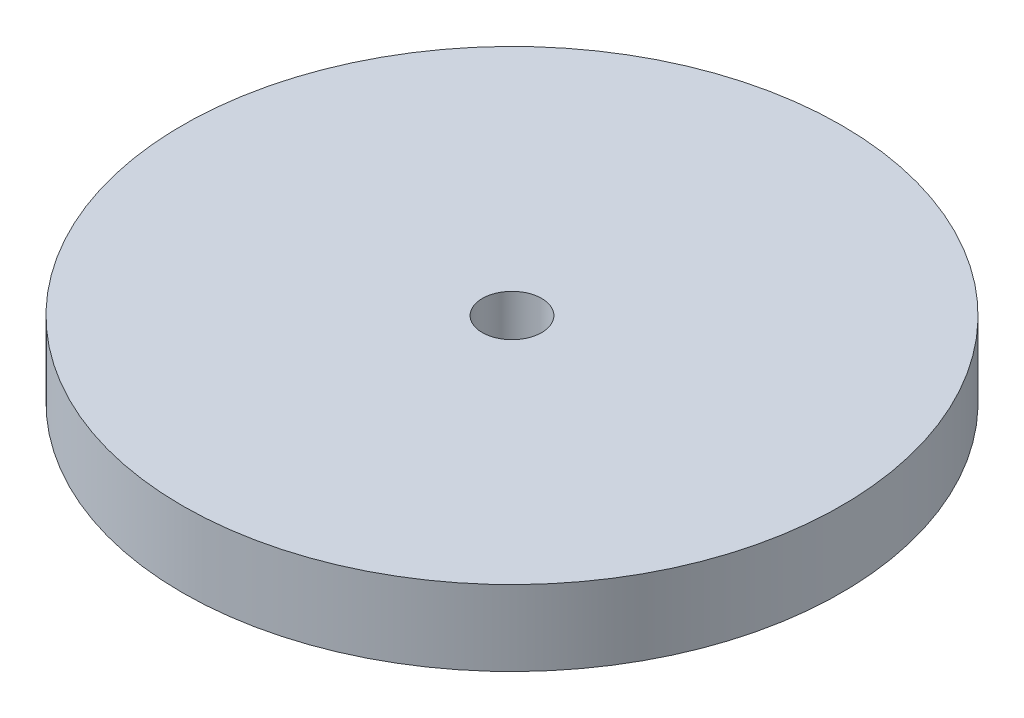
SolidWorks part; units mm, degrees
ref_plane "Front Plane" through (0, 0, 0) normal (0, 0, 1) x (1, 0, 0)
ref_plane "Top Plane" through (0, 0, 0) normal (0, 1, 0) x (1, 0, 0)
ref_plane "Right Plane" through (0, 0, 0) normal (1, 0, 0) x (0, 0, -1)
sketch "Sketch2" plane through (0, 0, 0) normal (0, 1, 0) x (1, 0, 0)
  circle A0 centre (0, 0) radius 33.3375
  dimension "D1" = 66.675
extrude "Boss-Extrude1" add sketch "Sketch2" along normal blind 7.62
sketch "Sketch3" plane through (0, 7.62, 0) normal (0, 1, 0) x (1, 0, 0)
  circle A0 centre (0, 0) radius 3
  dimension "D1" = 6
extrude "Cut-Extrude1" cut sketch "Sketch3" against normal up to next
